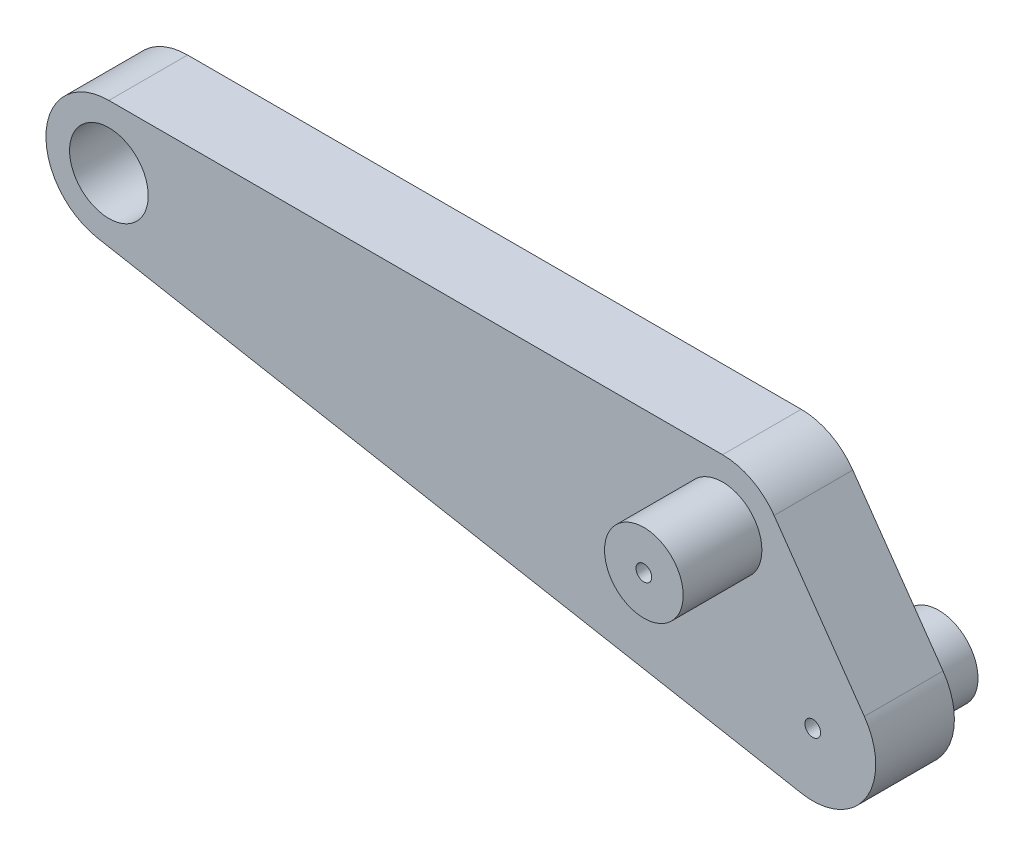
SolidWorks part; units mm, degrees
material "ABS"
ref_plane "Front Plane" through (0, 0, 0) normal (0, 0, 1) x (1, 0, 0)
ref_plane "Top Plane" through (0, 0, 0) normal (0, 1, 0) x (1, 0, 0)
ref_plane "Right Plane" through (0, 0, 0) normal (1, 0, 0) x (0, 0, -1)
sketch "Sketch1" plane through (0, 0, 0) normal (0, 0, 1) x (1, 0, 0)
  line L0 (0, 0) -> (-39, 0)
  line L1 (0, 0) -> (5.7358, -8.1915)
  dimension "D1" = 39
  dimension "D2" = 10
  dimension "D3" = 125
sketch "Sketch2" plane through (0, 0, 0) normal (0, 0, 1) x (1, 0, 0)
  line L0 (-39, 4) -> (0, 4)
  line L1 (3.2766, 2.2943) -> (9.0124, -5.8972)
  line L2 (5.0153, -12.1261) -> (-39.7205, -3.9346)
  circle A0 centre (-39, 0) radius 2.5
  arc A1 (-39, 4) -> (-39.7205, -3.9346) centre (-39, 0) ccw
  circle A2 centre (0, 0) radius 2.5
  arc A3 (3.2766, 2.2943) -> (0, 4) centre (0, 0) ccw
  circle A4 centre (5.7358, -8.1915) radius 2.5
  arc A5 (5.0153, -12.1261) -> (9.0124, -5.8972) centre (5.7358, -8.1915) ccw
  dimension "D1" = 5
  dimension "D2" = 8
  dimension "D3" = 5
  dimension "D4" = 8
  dimension "D5" = 5
  dimension "D6" = 8
extrude "Boss-Extrude1" add sketch "Sketch2" along normal blind 5
sketch "Sketch3" plane through (0, 0, 5) normal (0, 0, 1) x (1, 0, 0)
  circle A0 centre (5.7358, -8.1915) radius 2.5
  circle A1 centre (5.7358, -8.1915) radius 0.5
  dimension "D1" = 1
  dimension "D2" = 5
extrude "Boss-Extrude2" add sketch "Sketch3" against normal blind 8
sketch "Sketch4" plane through (0, 0, 0) normal (0, 0, -1) x (-1, 0, 0)
  circle A0 centre (0, 0) radius 2.5
  circle A1 centre (0, 0) radius 0.5
  dimension "D1" = 1
  dimension "D2" = 5
extrude "Boss-Extrude3" add sketch "Sketch4" against normal blind 10
